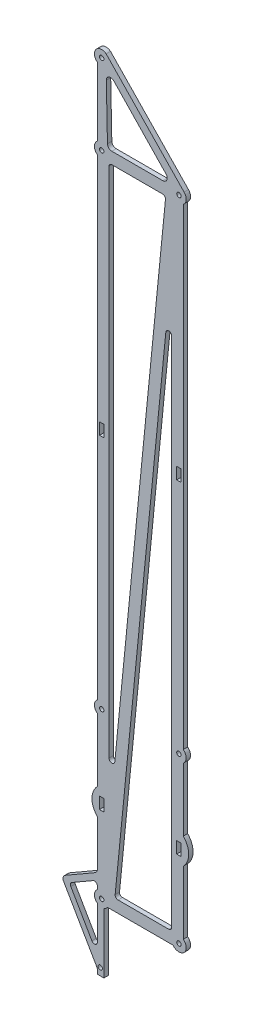
SolidWorks part; units mm, degrees
ref_plane "前视基准面" through (0, 0, 0) normal (0, 0, 1) x (1, 0, 0)
ref_plane "上视基准面" through (0, 0, 0) normal (0, 1, 0) x (1, 0, 0)
ref_plane "右视基准面" through (0, 0, 0) normal (1, 0, 0) x (0, 0, -1)
sketch "草图1" plane through (0, 0, 0) normal (0, 0, 1) x (1, 0, 0)
  line L7 (-3, -448) -> (-3, 3) construction
  line L8 (0, -445) -> (0, -332.18) construction
  line L12 (-3, -4) -> (-3, -328.18)
  line L13 (-3, -336.18) -> (-3, -441) construction
  line L20 (0, 0) -> (53, 0) construction
  line L21 (26.5, 0) -> (26.5, -16.3301) construction
  line L22 (53, -445) -> (53, -332.18) construction
  line L27 (56, -448) -> (56, 3) construction
  line L29 (53, -445) -> (53, 0) construction
  line L35 (56, -4) -> (56, -328.18)
  line L36 (6.9382, 3) -> (41.9698, 3)
  line L37 (4, -448) -> (49, -448)
  line L38 (0, -445) -> (5, -445) construction
  line L39 (5, -445) -> (5, -440) construction
  line L40 (53, -5) -> (48, -5) construction
  line L41 (5, -440) -> (48, -5) construction
  line L42 (48, -5) -> (5, -5) construction
  line L43 (5, -5) -> (5, -440) construction
  line L44 (5, -440) -> (48, -440) construction
  line L45 (48, -440) -> (48, -5) construction
  line L46 (8.9806, -440.3935) -> (51.9806, -5.3935) construction
  line L47 (48, -86.2261) -> (48, -438)
  line L48 (11.2269, -440) -> (46, -440)
  line L49 (9.2366, -437.8033) -> (44.0097, -86.0293)
  line L50 (1.0194, -439.6065) -> (44.0194, -4.6065) construction
  line L51 (43.7634, -7.1967) -> (8.9903, -358.9707)
  line L52 (5, -358.7739) -> (5, -7)
  line L53 (7, -5) -> (41.7731, -5)
  line L54 (0, -445) -> (53, -445) construction
  line L55 (1.5, -486.25) -> (1.5, -449.7697) construction
  line L56 (1.5, -486.25) -> (1.5, -491.25) construction
  line L57 (-3, -487.75) -> (-3, -449) construction
  line L58 (1.5, -491.25) -> (-3, -491.25)
  line L59 (-3, -491.25) -> (-3, -488.5538)
  line L61 (1.5, -485.1496) -> (1.5, -449.7697)
  line L63 (1.5, -487.3504) -> (1.5, -491.25)
  line L64 (-3.4019, -487.0538) -> (-20.6463, -457.1857)
  line L65 (-20.6463, -457.1857) -> (-26.1817, -447.5981)
  line L66 (-25.0836, -443.5) -> (-4.5, -431.616)
  line L67 (0.4641, -485.75) -> (-17.1822, -455.1857) construction
  line L68 (-17.1822, -455.1857) -> (-21.2176, -448.1962)
  line L69 (-22.2176, -446.4641) -> (-1, -434.2141) construction
  line L70 (-3, -429.0179) -> (-3, -336.18) construction
  line L71 (-20.4856, -445.4641) -> (-6, -437.1009)
  line L72 (-3, -438.8329) -> (-3, -441)
  line L73 (-17.1822, -455.1857) -> (-6.7321, -473.2859)
  line L74 (-3, -472.2859) -> (-3, -449)
  line L75 (-17.1822, -455.1857) -> (-22.2176, -446.4641) construction
  line L76 (-27.6817, -445) -> (-3, -430.75) construction
  line L77 (-20.6463, -457.1857) -> (-27.6817, -445) construction
  line L78 (-3, -487.75) -> (-20.6463, -457.1857) construction
  line L79 (0, 0) -> (0, 55) construction
  line L80 (-3, 4) -> (-3, 51)
  line L81 (3.9388, 5.9375) -> (3.1603, 43.3046)
  line L82 (8.3256, 45.4428) -> (44.1358, 8.0757)
  line L83 (3, 59) -> (56.5355, 3.5355)
  line L84 (0, -486.25) -> (-1, -486.25) construction
  line L85 (1.5, -487.3504) -> (1.5, -485.1496)
  line L86 (26.5, -445) -> (26.5, -419.2738) construction
  line L87 (-1.52, -388.59) -> (-1.52, -384.57)
  line L88 (-1.52, -384.57) -> (1.52, -384.57)
  line L89 (1.52, -384.57) -> (1.52, -392.61)
  line L90 (1.52, -392.61) -> (-1.52, -392.61)
  line L91 (-1.52, -392.61) -> (-1.52, -388.59)
  line L92 (54.52, -392.61) -> (54.52, -388.59)
  line L93 (54.52, -388.59) -> (54.52, -384.57)
  line L94 (54.52, -384.57) -> (51.48, -384.57)
  line L95 (51.48, -392.61) -> (54.52, -392.61)
  line L96 (51.48, -384.57) -> (51.48, -392.61)
  line L97 (-3, -397.5102) -> (-3, -429.0179)
  line L98 (-3, -379.6698) -> (-3, -336.18)
  line L99 (56, -397.5102) -> (56, -441)
  line L100 (56, -379.6698) -> (56, -336.18)
  line L101 (0, 0) -> (0, -332.18) construction
  line L102 (0, -166.09) -> (-25.0836, -166.09) construction
  line L103 (54.52, -162.07) -> (51.48, -162.07)
  line L104 (-1.52, -162.07) -> (1.52, -162.07)
  line L105 (-1.52, -162.07) -> (-1.52, -170.11)
  line L106 (-1.52, -170.11) -> (1.52, -170.11)
  line L107 (1.52, -162.07) -> (1.52, -170.11)
  line L108 (54.52, -170.11) -> (51.48, -170.11)
  line L109 (54.52, -162.07) -> (54.52, -170.11)
  line L110 (51.48, -162.07) -> (51.48, -170.11)
  circle A0 centre (0, 0) radius 1.5
  circle A3 centre (0, -445) radius 1.5
  circle A4 centre (0, -332.18) radius 1.5
  circle A6 centre (0, 0) radius 5 construction
  circle A9 centre (0, -445) radius 5 construction
  circle A11 centre (0, -332.18) radius 5 construction
  arc A12 (4, -448) -> (-3, -441) centre (0, -445) cw construction
  arc A17 (-3, -336.18) -> (-3, -328.18) centre (0, -332.18) cw
  circle A24 centre (53, -332.18) radius 5 construction
  circle A25 centre (53, -445) radius 5 construction
  circle A26 centre (53, 0) radius 5 construction
  arc A27 (56, -336.18) -> (56, -328.18) centre (53, -332.18) ccw
  arc A29 (49, -448) -> (56, -441) centre (53, -445) ccw
  circle A30 centre (53, -332.18) radius 1.5
  circle A31 centre (53, -445) radius 1.5
  circle A32 centre (53, 0) radius 1.5
  arc A33 (48, -438) -> (46, -440) centre (46, -438) cw
  arc A34 (11.2269, -440) -> (9.2366, -437.8033) centre (11.2269, -438) cw
  arc A35 (48, -86.2261) -> (44.0097, -86.0293) centre (46, -86.2261) ccw
  arc A36 (43.7634, -7.1967) -> (41.7731, -5) centre (41.7731, -7) ccw
  arc A37 (7, -5) -> (5, -7) centre (7, -7) ccw
  arc A38 (8.9903, -358.9707) -> (5, -358.7739) centre (7, -358.7739) cw
  arc A42 (1.5, -449.7697) -> (4, -448) centre (0, -445) ccw
  arc A43 (-3, -449) -> (-3, -441) centre (0, -445) cw
  arc A46 (-3, -472.2859) -> (-6.7321, -473.2859) centre (-5, -472.2859) cw
  arc A47 (-21.2176, -448.1962) -> (-20.4856, -445.4641) centre (-19.4856, -447.1962) cw
  arc A48 (-3, -438.8329) -> (-6, -437.1009) centre (-5, -438.8329) ccw
  arc A49 (-3, -429.0179) -> (-4.5, -431.616) centre (-6, -429.0179) cw
  arc A50 (-25.0836, -443.5) -> (-26.1817, -447.5981) centre (-23.5836, -446.0981) ccw
  arc A51 (-3, -488.5538) -> (-3.4019, -487.0538) centre (-6, -488.5538) ccw
  circle A52 centre (0, 55) radius 1.5
  circle A53 centre (0, 55) radius 5 construction
  arc A54 (56.5355, 3.5355) -> (56, -4) centre (53, 0) cw
  arc A55 (-3, 51) -> (3, 59) centre (0, 55) cw
  arc A56 (-3, -4) -> (-3, 4) centre (0, 0) cw
  circle A57 centre (-1, -486.25) radius 1.5
  arc A58 (8.3256, 45.4428) -> (3.1603, 43.3046) centre (6.1597, 43.3671) ccw
  arc A59 (44.1358, 8.0757) -> (41.9698, 3) centre (41.9698, 6) cw
  arc A60 (6.9382, 3) -> (3.9388, 5.9375) centre (6.9382, 6) cw
  circle A61 centre (1.52, -388.59) radius 10 construction
  arc A62 (-3, -397.5102) -> (-3, -379.6698) centre (5.9202, -388.59) cw
  arc A63 (56, -397.5102) -> (56, -379.6698) centre (47.0798, -388.59) ccw
  point P59 (9.0195, -440)
  point P62 (48, -45.6623)
  point P65 (43.9805, -5)
  point P71 (5, -399.3377)
  point P100 (-3, -479.75)
  point P106 (-3, -435.3688)
  point P110 (-3, -430.75)
  point P128 (3, 51)
  point P131 (49, 3)
  point P134 (4, 3)
  dimension "D1" = 445
  dimension "D7" = 3
  dimension "D2" = 53
  dimension "D3" = 2
  dimension "D4" = 30
  dimension "D6" = 2
  dimension "D8" = 3
  dimension "D5" = 4
extrude "凸台-拉伸1" add sketch "草图1" along normal blind 3
